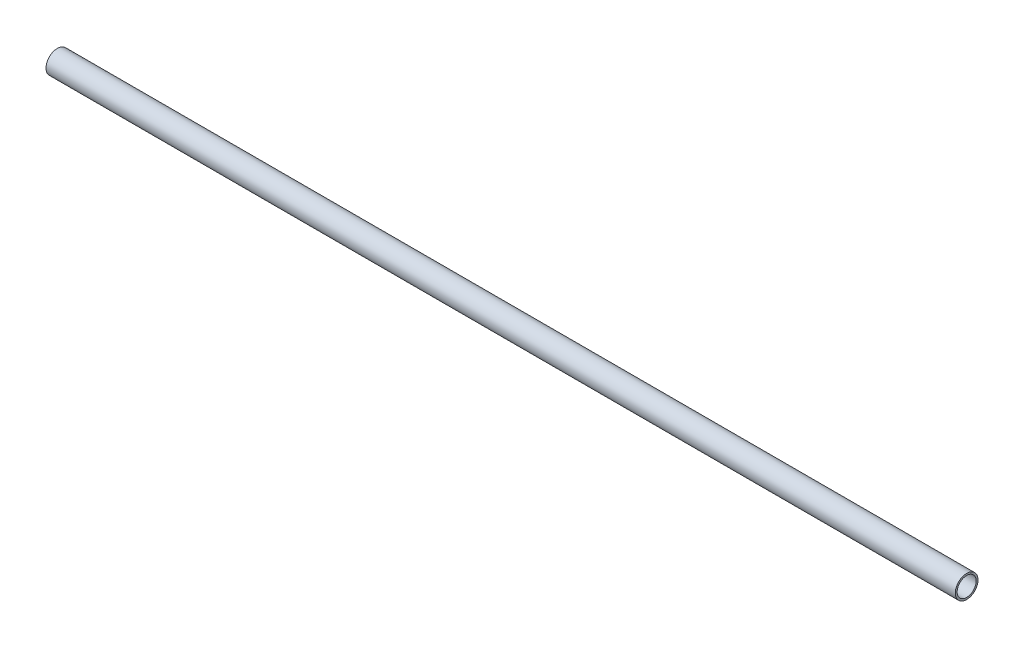
SolidWorks part; units mm, degrees
material "PVC Rigid"
ref_plane "Front Plane" through (0, 0, 0) normal (0, 0, 1) x (1, 0, 0)
ref_plane "Top Plane" through (0, 0, 0) normal (0, 1, 0) x (1, 0, 0)
ref_plane "Right Plane" through (0, 0, 0) normal (1, 0, 0) x (0, 0, -1)
sketch "Sketch1" plane through (0, 0, 0) normal (1, 0, 0) x (0, 0, -1)
  circle A0 centre (0, 0) radius 24.13
  circle A1 centre (0, 0) radius 20.193
  dimension "D1" = 48.26
  dimension "D2" = 40.386
extrude "Boss-Extrude1" add sketch "Sketch1" along normal blind 1930.4
